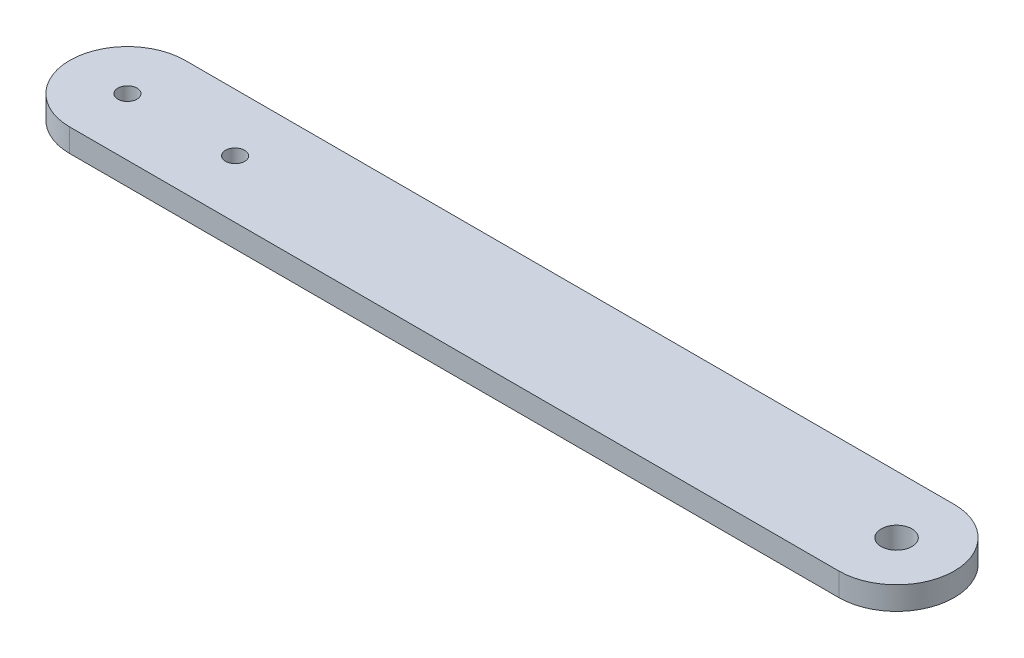
SolidWorks part; units mm, degrees
ref_plane "Front Plane" through (0, 0, 0) normal (0, 0, 1) x (1, 0, 0)
ref_plane "Top Plane" through (0, 0, 0) normal (0, 1, 0) x (1, 0, 0)
ref_plane "Right Plane" through (0, 0, 0) normal (1, 0, 0) x (0, 0, -1)
sketch "Sketch1" plane through (0, 0, 0) normal (0, 1, 0) x (1, 0, 0)
  line L0 (0, 0) -> (100, 0) construction
  line L1 (0, 7.5) -> (100, 7.5)
  line L2 (0, -7.5) -> (100, -7.5)
  arc A0 (0, 7.5) -> (0, -7.5) centre (0, 0) ccw
  arc A1 (100, -7.5) -> (100, 7.5) centre (100, 0) ccw
  circle A2 centre (100, 0) radius 2
  circle A3 centre (0, 0) radius 1.25
  circle A4 centre (14, 0) radius 1.25
  point P3 (50, 0)
  dimension "D2" = 4
  dimension "D3" = 7.5
  dimension "D4" = 2.5
  dimension "D5" = 2.5
  dimension "D1" = 100
  dimension "D6" = 14
extrude "Boss-Extrude1" add sketch "Sketch1" along normal blind 3
